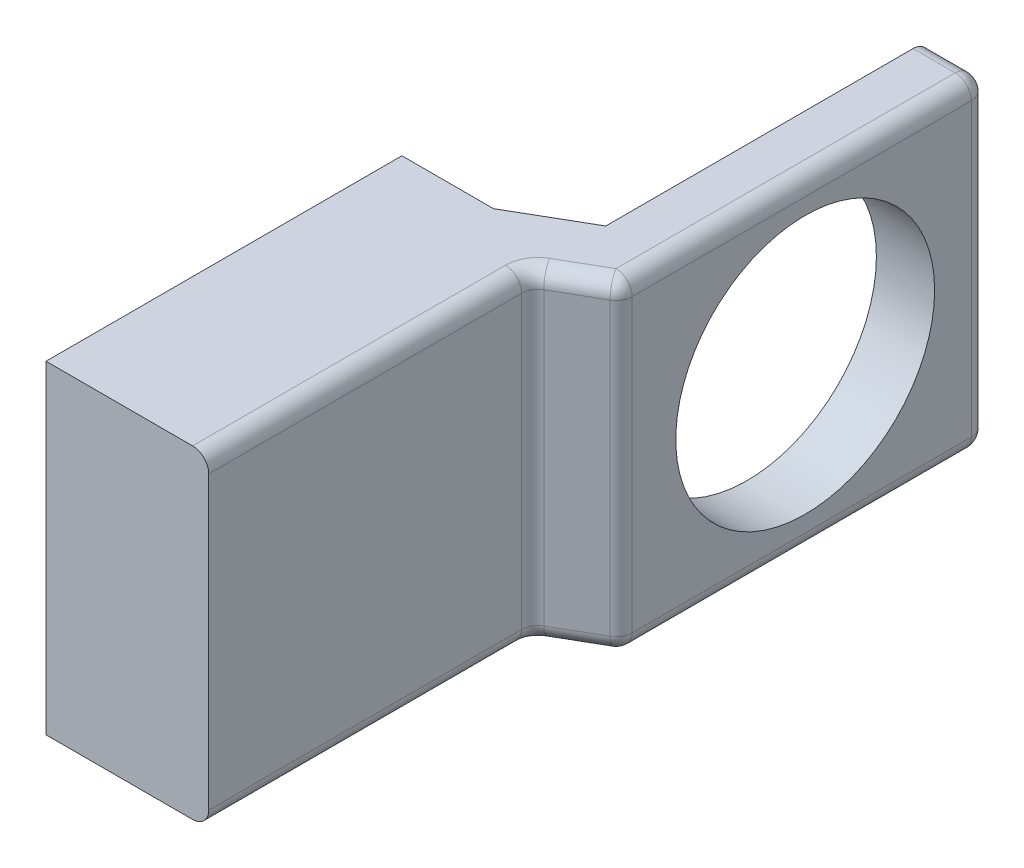
SolidWorks part; units mm, degrees
ref_plane "Front Plane" through (0, 0, 0) normal (0, 0, 1) x (1, 0, 0)
ref_plane "Top Plane" through (0, 0, 0) normal (0, 1, 0) x (1, 0, 0)
ref_plane "Right Plane" through (0, 0, 0) normal (1, 0, 0) x (0, 0, -1)
sketch "Sketch1" plane through (0, 0, 0) normal (0, 1, 0) x (1, 0, 0)
  line L0 (0, 141.8582) -> (0, -116.9338) construction
  line L1 (-186.6185, 0) -> (241.0969, 0) construction
  line L2 (50.3, -110) -> (50.3, -10.3923)
  line L3 (50.3, -10.3923) -> (68.3, 0)
  line L4 (68.3, 0) -> (68.3, 112.7017)
  line L5 (68.3, 112.7017) -> (50.3, 112.7017)
  line L6 (50.3, 112.7017) -> (50.3, 12.7017)
  line L7 (50.3, 12.7017) -> (28.3, 0)
  line L10 (28.3, 0) -> (0, 0)
  line L11 (0, 0) -> (0, -110)
  line L12 (0, -110) -> (50.3, -110)
  dimension "D1" = 30
  dimension "D2" = 18
  dimension "D3" = 28.3
  dimension "D4" = 20
  dimension "D5" = 100
  dimension "D6" = 110
extrude "Boss-Extrude1" add sketch "Sketch1" along normal blind 100
sketch "Sketch2" plane through (68.3, 0, 0) normal (1, 0, 0) x (0, 0, -1)
  line L0 (0, 50) -> (112.7017, 50) construction
  line L1 (0, 100) -> (0, 0) construction
  line L2 (112.7017, 100) -> (112.7017, 0) construction
  line L3 (56.3509, 100) -> (56.3509, 0) construction
  line L4 (0, 100) -> (112.7017, 100) construction
  line L5 (0, 0) -> (112.7017, 0) construction
  circle A0 centre (56.3509, 50) radius 40
  dimension "D1" = 80
extrude "Cut-Extrude1" cut sketch "Sketch2" against normal up to next
fillet "Fillet2" radius 5 11 edges at (50.3, 0, 60.1962) (50.3, 100, 60.1962) (59.3, 0, 5.1962) (59.3, 100, 5.1962) (68.3, 0, -56.3509) (68.3, 50, -112.7017) (68.3, 100, -56.3509) (68.3, 50, 0) (50.3, 50, 10.3923) (59.3, 0, -112.7017) (59.3, 100, -112.7017)
